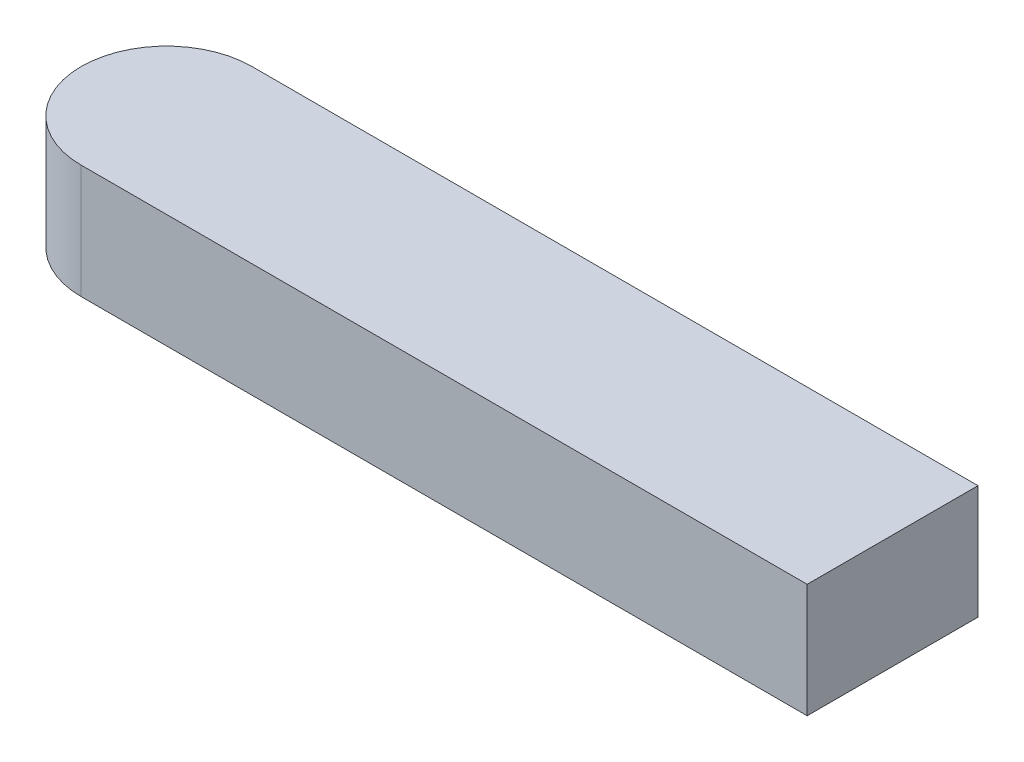
SolidWorks part; units mm, degrees
material "St-52"
ref_plane "Front Plane" through (0, 0, 0) normal (0, 0, 1) x (1, 0, 0)
ref_plane "Top Plane" through (0, 0, 0) normal (0, 1, 0) x (1, 0, 0)
ref_plane "Right Plane" through (0, 0, 0) normal (1, 0, 0) x (0, 0, -1)
sketch "Sketch1" plane through (0, 0, 0) normal (0, 1, 0) x (1, 0, 0)
  line L0 (-14.2703, 0) -> (36.7297, 0) construction
  line L1 (-14.2703, 6) -> (36.7297, 6)
  line L2 (-14.2703, -6) -> (36.7297, -6)
  line L3 (36.7297, -6) -> (36.7297, 6)
  arc A0 (-14.2703, 6) -> (-14.2703, -6) centre (-14.2703, 0) ccw
  point P3 (11.2297, 0)
  dimension "D1" = 6
  dimension "D2" = 51
extrude "Boss-Extrude1" add sketch "Sketch1" along normal mid plane 8
